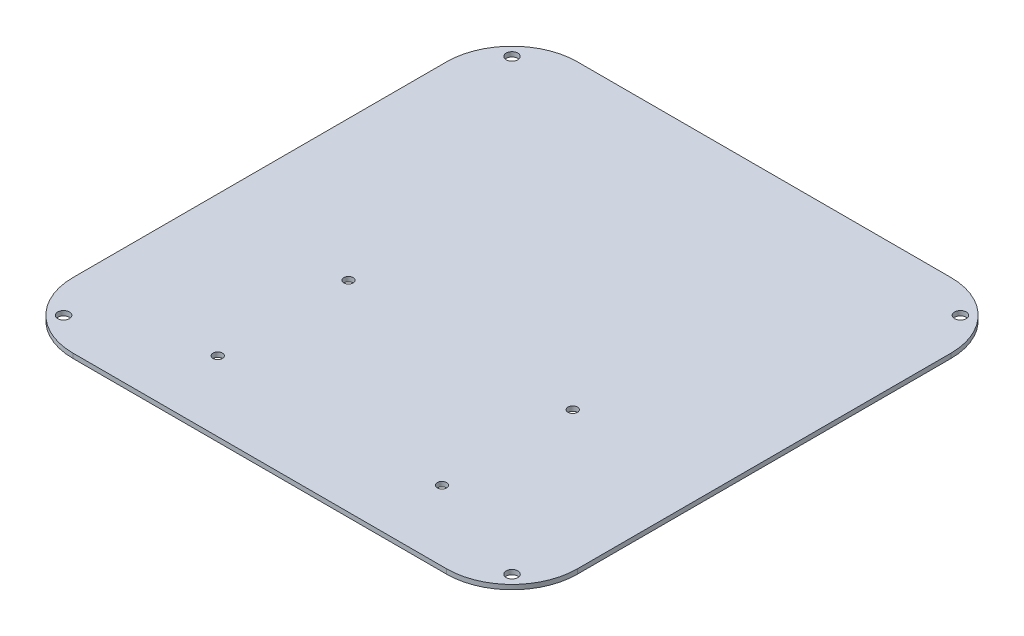
SolidWorks part; units mm, degrees
ref_plane "Front Plane" through (0, 0, 0) normal (0, 0, 1) x (1, 0, 0)
ref_plane "Top Plane" through (0, 0, 0) normal (0, 1, 0) x (1, 0, 0)
ref_plane "Right Plane" through (0, 0, 0) normal (1, 0, 0) x (0, 0, -1)
sketch "Sketch1" plane through (0, 0, 0) normal (0, 1, 0) x (1, 0, 0)
  line L65 (-80, -108) -> (80, -108)
  line L66 (-108, -80) -> (-108, 80)
  line L67 (-80, 108) -> (80, 108)
  line L68 (108, -80) -> (108, 80)
  line L69 (-108, -108) -> (108, 108) construction
  line L70 (-108, 108) -> (108, -108) construction
  line L71 (-48, -78) -> (48, -78)
  line L78 (-48, -78) -> (-48, -22)
  line L79 (-48, -22) -> (48, -22)
  line L80 (48, -78) -> (48, -22)
  line L81 (-48, -78) -> (48, -22) construction
  line L82 (-48, -22) -> (48, -78) construction
  arc A68 (-108, -80) -> (-80, -108) centre (-80, -80) ccw
  arc A69 (80, -108) -> (108, -80) centre (80, -80) ccw
  arc A70 (108, 80) -> (80, 108) centre (80, 80) ccw
  arc A71 (-108, 80) -> (-80, 108) centre (-80, 80) cw
  circle A72 centre (-48, -22) radius 2
  circle A73 centre (-48, -78) radius 2
  circle A74 centre (48, -78) radius 2
  circle A75 centre (48, -22) radius 2
  circle A76 centre (-96, 96) radius 2.5
  circle A77 centre (96, 96) radius 2.5
  circle A78 centre (96, -96) radius 2.5
  circle A79 centre (-96, -96) radius 2.5
  point P0 (0, 0)
  point P17 (0, -50)
  dimension "D1" = 216
  dimension "D2" = 216
  dimension "D3" = 28
  dimension "D4" = 96
  dimension "D10" = 4
  dimension "D11" = 4
  dimension "D8" = 4
  dimension "D9" = 4
  dimension "D13" = 5
  dimension "D15" = 5
  dimension "D17" = 5
  dimension "D19" = 5
  dimension "D5" = 56
  dimension "D6" = 0
  dimension "D7" = 50
  dimension "D12" = 96
  dimension "D14" = 96
  dimension "D16" = 96
  dimension "D18" = 96
extrude "Boss-Extrude1" add sketch "Sketch1" along normal blind 2 contours A71 L66 A68 L65 A69 L68 A70 L67 A79 A78 A77 A76 A75 L80 A74 L71 A73 L78 A72 L79 | A75 L79 A72 L78 A73 L71 A74 L80
